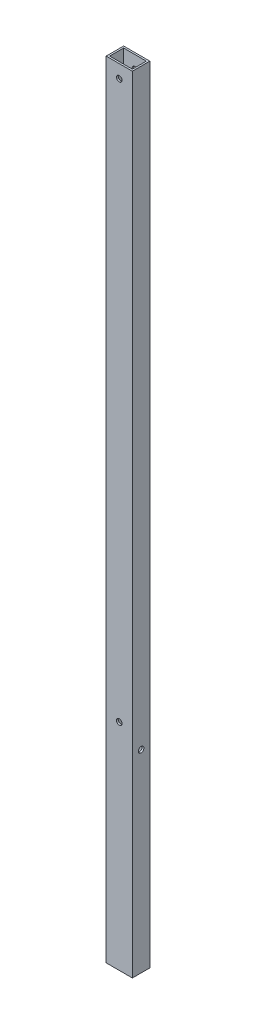
SolidWorks part; units mm, degrees
ref_plane "正面" through (0, 0, 0) normal (0, 0, 1) x (1, 0, 0)
ref_plane "平面" through (0, 0, 0) normal (0, 1, 0) x (1, 0, 0)
ref_plane "右側面" through (0, 0, 0) normal (1, 0, 0) x (0, 0, -1)
sketch "ｽｹｯﾁ1" plane through (0, 0, 464.4987) normal (0, 0, 1) x (1, 0, 0)
  line L0 (0, 0) -> (-15, 0)
  line L1 (-15, 0) -> (-15, 475.9582)
  line L2 (-15, 475.9582) -> (0, 475.9582)
  line L3 (0, 475.9582) -> (0, 0)
  circle A6 centre (-7.5, 468.4582) radius 1.6
  circle A8 centre (-7.5, 149.2749) radius 1.6
  dimension "D1" = 7.5
  dimension "D5" = 7.5
  dimension "D7" = 326.6833
  dimension "D10" = 3.2
  dimension "D11" = 3.2
  dimension "D2" = 15
  dimension "D6" = 7.5
extrude "ﾎﾞｽ - 押し出し1" add sketch "ｽｹｯﾁ1" against normal blind 10
sketch "ｽｹｯﾁ3" plane through (0, 0, 454.4987) normal (0, 0, -1) x (-1, 0, 0)
  line L0 (7.5, 149.2749) -> (7.5, 136.7749) construction
  line L1 (0, 0) -> (0, 475.9582) construction
  line L2 (0, 136.7749) -> (15, 136.7749) construction
  line L3 (15, 475.9582) -> (15, 0) construction
  point P0 (7.5, 136.7749)
  point P11 (7.5, 136.7749)
  dimension "D1" = 12.5
sketch "ｽｹｯﾁ2" plane through (0, 0, 464.4987) normal (0, 0, 1) x (1, 0, 0)
  line L0 (-15, 475.9582) -> (-15, 0) construction
  line L1 (0, 0) -> (-15, 0)
  line L2 (0, 0) -> (0, 25.9582)
  line L3 (0, 25.9582) -> (-15, 25.9582)
  line L4 (-15, 0) -> (-15, 25.9582)
  line L6 (0, 475.9582) -> (-15, 475.9582) construction
  dimension "D1" = 450
extrude "ｶｯﾄ - 押し出し1" cut sketch "ｽｹｯﾁ2" against normal blind 100
sketch "ｽｹｯﾁ4" plane through (-15, 0, 0) normal (-1, 0, 0) x (0, 0, 1)
  line L0 (454.4987, 136.7749) -> (464.4987, 136.7749) construction
  line L1 (464.4987, 475.9582) -> (464.4987, 25.9582) construction
  circle A0 centre (459.4987, 136.7749) radius 1.6
  dimension "D1" = 3.2
extrude "ｶｯﾄ - 押し出し2" cut sketch "ｽｹｯﾁ4" against normal blind 15
sketch "ｽｹｯﾁ5" plane through (0, 475.9582, 0) normal (0, 1, 0) x (1, 0, 0)
  line L8 (-14, -463.4987) -> (-1, -463.4987)
  line L9 (-1, -463.4987) -> (-1, -455.4987)
  line L10 (-1, -455.4987) -> (-14, -455.4987)
  line L11 (-14, -455.4987) -> (-14, -463.4987)
  line L12 (-14, -463.4987) -> (-1, -463.4987)
  line L13 (-1, -463.4987) -> (-1, -455.4987)
  line L14 (-1, -455.4987) -> (-14, -455.4987)
  line L15 (-14, -455.4987) -> (-14, -463.4987)
  dimension "D1" = 1
extrude "ｶｯﾄ - 押し出し3" cut sketch "ｽｹｯﾁ5" against normal blind 1000
